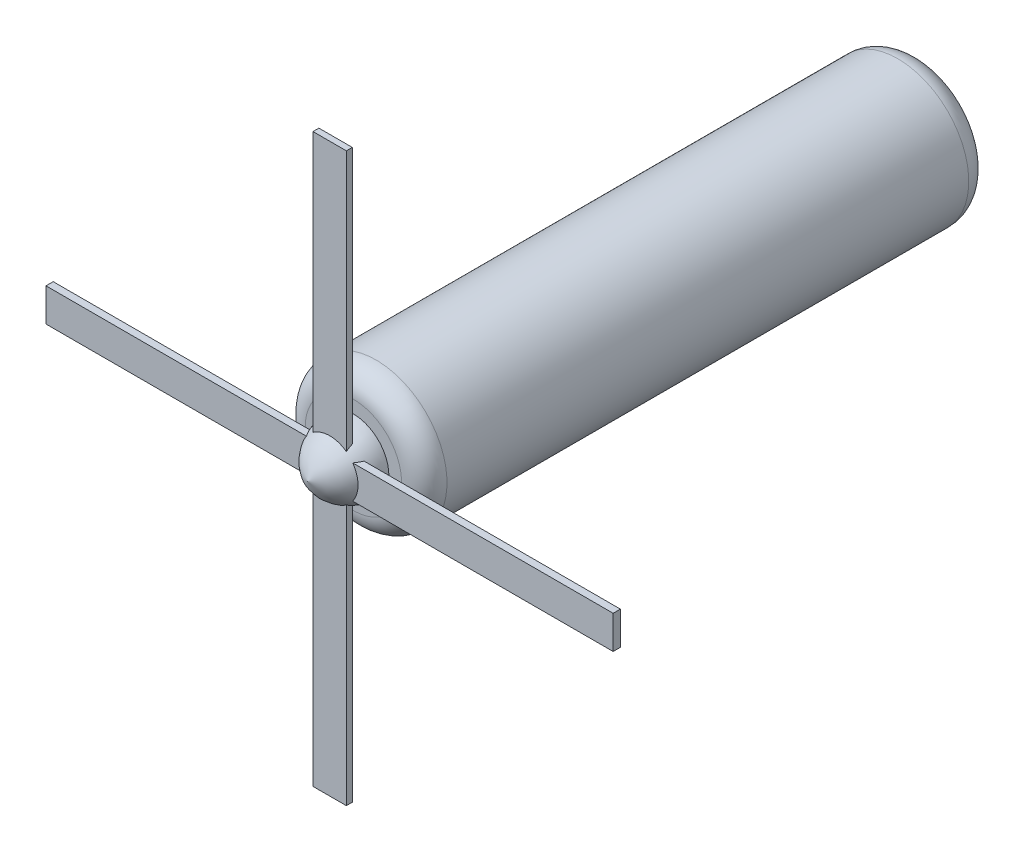
SolidWorks part; units mm, degrees
ref_plane "Front Plane" through (0, 0, 0) normal (0, 0, 1) x (1, 0, 0)
ref_plane "Top Plane" through (0, 0, 0) normal (0, 1, 0) x (1, 0, 0)
ref_plane "Right Plane" through (0, 0, 0) normal (1, 0, 0) x (0, 0, -1)
sketch "Sketch1" plane through (0, 0, 0) normal (0, 1, 0) x (1, 0, 0)
  line L0 (0, 0) -> (-37.9259, -13.6498) construction
  line L1 (0, 0) -> (0, 161.2461)
  line L2 (125, 161.2461) -> (0, 161.2461)
  spline S0 degree 3 poles (0, 0) (25.6503, 9.2317) (88.992, 38.31) (123.5244, 115.2404) (125, 161.2461) knots 0 0 0 0 0.343948 1 1 1 1
  point P3 (-118.3913, -26.2848)
  point P6 (-37.9259, -13.6498)
  point P8 (65.8147, 34.8955)
  point P10 (115.0249, 109.3759)
  point P11 (125, 161.2461)
  dimension "D1" = 125
revolve "Revolve1" add sketch "Sketch1" angle 360 about L1
sketch "Sketch2" plane through (0, 0, -161.2461) normal (0, 0, -1) x (-1, 0, 0)
  circle A0 centre (0, 0) radius 250
  dimension "D1" = 500
extrude "Boss-Extrude1" add sketch "Sketch2" along normal blind 2000
fillet "Fillet1" radius 80 2 edges at (-250, 0, -161.2461) (-250, 0, -2161.2461)
sketch "Sketch3" plane through (0, 0, 0) normal (0, 1, 0) x (1, 0, 0)
  line L1 (58.8538, 77.4921) -> (-58.8538, 77.4921)
  line L2 (58.8538, 77.4921) -> (58.8538, 98.4179)
  line L3 (58.8538, 98.4179) -> (-58.8538, 98.4179)
  line L4 (-58.8538, 77.4921) -> (-58.8538, 98.4179)
  line L5 (58.8538, 77.4921) -> (-58.8538, 98.4179) construction
  line L6 (58.8538, 98.4179) -> (-58.8538, 77.4921) construction
  point P0 (0, 87.955)
extrude "Boss-Extrude2" add sketch "Sketch3" along normal mid plane 2000
sketch "Sketch4" plane through (0, 0, 0) normal (1, 0, 0) x (0, 0, -1)
  line L0 (102.6463, -58.403) -> (77.1558, -58.403)
  line L1 (102.6463, -58.403) -> (102.6463, 58.403)
  line L2 (102.6463, 58.403) -> (77.1558, 58.403)
  line L3 (77.1558, -58.403) -> (77.1558, 58.403)
  line L4 (102.6463, -58.403) -> (77.1558, 58.403) construction
  line L5 (102.6463, 58.403) -> (77.1558, -58.403) construction
  point P0 (89.901, 0)
  point P5 (42.6277, -143.5384)
  point P6 (116.8125, 0)
  point P7 (130.207, -47.7163)
  point P8 (0, 0)
  point P10 (0, 0)
  point P11 (0, 0)
  point P12 (46.7944, -58.403)
  point P13 (89.901, 0)
extrude "Boss-Extrude3" add sketch "Sketch4" along normal mid plane 2000
